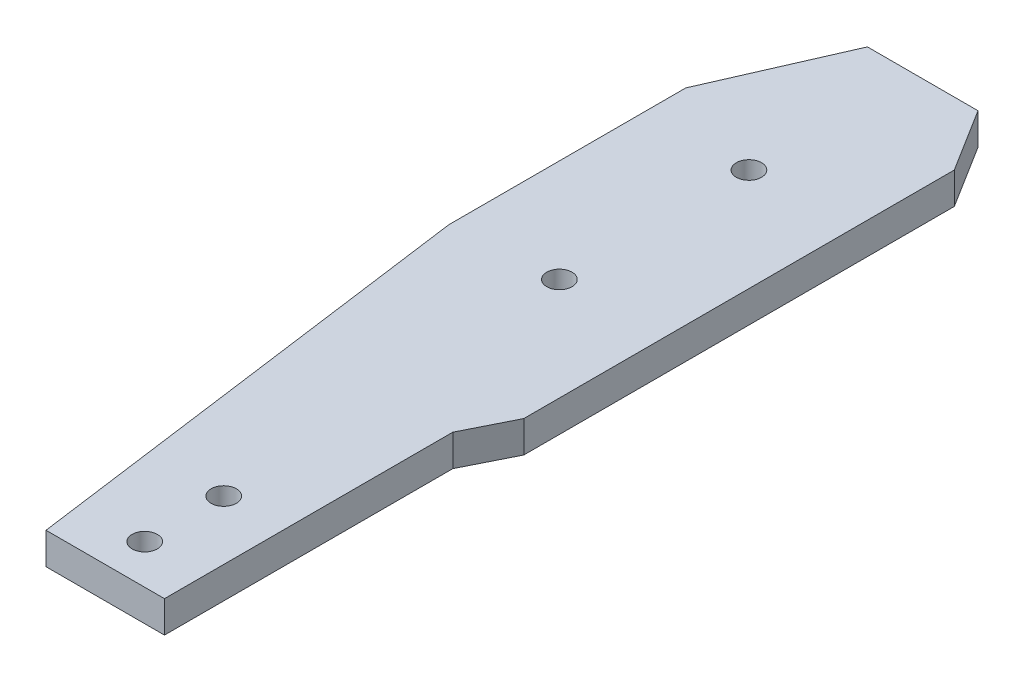
SolidWorks part; units mm, degrees
ref_plane "Front Plane" through (0, 0, 0) normal (0, 0, 1) x (1, 0, 0)
ref_plane "Top Plane" through (0, 0, 0) normal (0, 1, 0) x (1, 0, 0)
ref_plane "Right Plane" through (0, 0, 0) normal (1, 0, 0) x (0, 0, -1)
sketch "Sketch1" plane through (0, 0, 0) normal (0, 1, 0) x (1, 0, 0)
  line L1 (0, -54.5) -> (-3, -60.5)
  line L2 (-3, -60.5) -> (-3, -97)
  line L3 (-3, -97) -> (-18, -97)
  line L4 (-18, -97) -> (-26, -38)
  line L5 (-26, -38) -> (-26, -8)
  line L6 (-26, -8) -> (-19, 8)
  line L7 (-19, 8) -> (-5, 8)
  line L8 (-5, 8) -> (0, 0)
  line L10 (0, 0) -> (0, -54.5)
  dimension "D2" = 105
  dimension "D3" = 6
  dimension "D4" = 3
  dimension "D5" = 15
  dimension "D6" = 30
  dimension "D7" = 16
  dimension "D8" = 14
  dimension "D9" = 8
  dimension "D10" = 5
  dimension "D11" = 36.5
  dimension "D12" = 26
extrude "Boss-Extrude1" add sketch "Sketch1" along normal blind 4 contours L6 L7 L8 L10 L1 L2 L3 L4 L5
sketch "Sketch2" plane through (0, 4, 0) normal (0, 1, 0) x (1, 0, 0)
  line L0 (-3, -97) -> (-18, -97) construction
  line L1 (-3, -60.5) -> (-3, -97) construction
  line L2 (0, 0) -> (0, -54.5) construction
  line L3 (-19, 8) -> (-5, 8) construction
  circle A0 centre (-13, -13) radius 1.6
  circle A1 centre (-13, -37) radius 1.6
  circle A2 centre (-10.5, -82) radius 1.6
  circle A3 centre (-10.5, -92) radius 1.6
  dimension "D1" = 3.2
  dimension "D2" = 3.2
  dimension "D3" = 3.2
  dimension "D4" = 3.2
  dimension "D5" = 5
  dimension "D6" = 10
  dimension "D7" = 7.5
  dimension "D8" = 13
  dimension "D9" = 21
  dimension "D10" = 24
extrude "Cut-Extrude1" cut sketch "Sketch2" against normal through all
